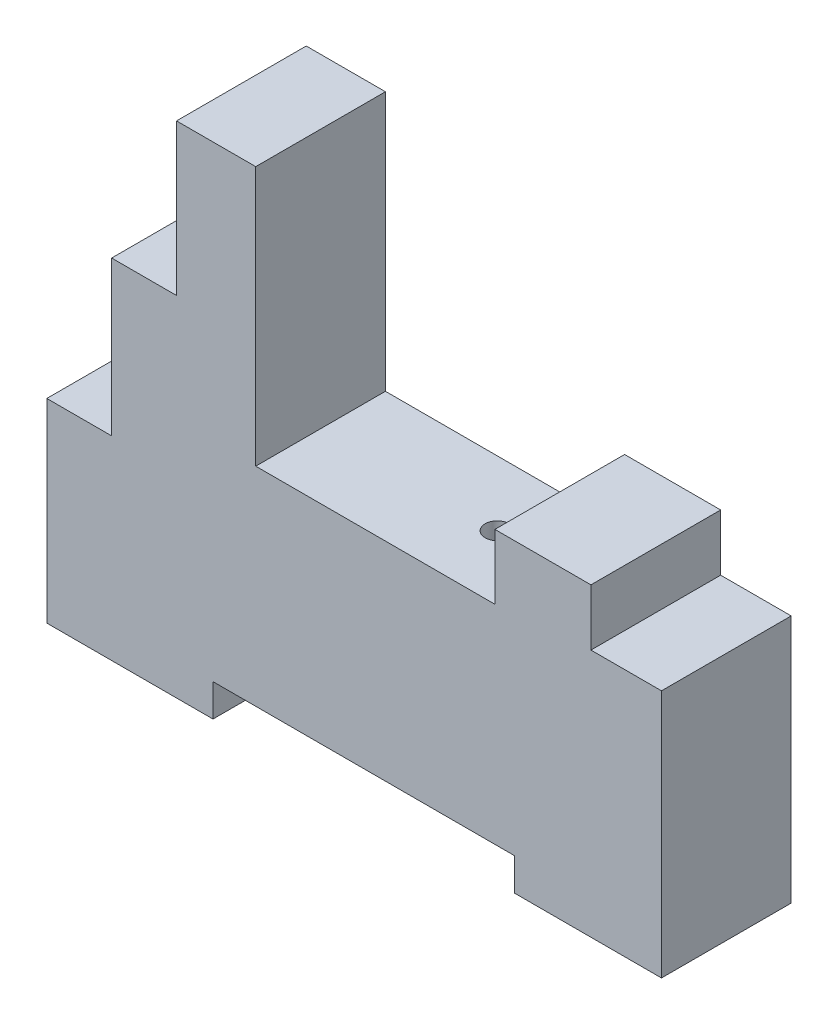
SolidWorks part; units mm, degrees
ref_plane "Front Plane" through (0, 0, 0) normal (0, 0, 1) x (1, 0, 0)
ref_plane "Top Plane" through (0, 0, 0) normal (0, 1, 0) x (1, 0, 0)
ref_plane "Right Plane" through (0, 0, 0) normal (1, 0, 0) x (0, 0, -1)
sketch "Sketch1" plane through (0, 0, 0) normal (0, 0, 1) x (1, 0, 0)
  line L0 (0, 0) -> (0, 24)
  line L1 (0, 24) -> (8, 24)
  line L2 (8, 24) -> (8, 43)
  line L3 (8, 43) -> (16, 43)
  line L4 (16, 43) -> (16, 61.65)
  line L5 (16, 61.65) -> (25.77, 61.65)
  line L6 (25.77, 61.65) -> (25.77, 29.65)
  line L7 (25.77, 29.65) -> (55.27, 29.65)
  line L8 (55.27, 29.65) -> (55.27, 37.65)
  line L9 (55.27, 37.65) -> (67.12, 37.65)
  line L10 (67.12, 37.65) -> (67.12, 30.68)
  line L11 (67.12, 30.68) -> (75.82, 30.68)
  line L12 (75.82, 30.68) -> (75.82, 0)
  line L13 (75.82, 0) -> (57.7, 0)
  line L14 (57.7, 0) -> (57.7, 4)
  line L15 (57.7, 4) -> (20.5, 4)
  line L16 (20.5, 4) -> (20.5, 0)
  line L17 (20.5, 0) -> (0, 0)
  dimension "D1" = 24
  dimension "D2" = 43
  dimension "D3" = 61.65
  dimension "D4" = 8
  dimension "D5" = 32
  dimension "D6" = 29.5
  dimension "D7" = 8
  dimension "D8" = 11.85
  dimension "D9" = 8.7
  dimension "D10" = 4
  dimension "D11" = 37.2
  dimension "D12" = 20.5
  dimension "D14" = 30.68
  dimension "D15" = 9.77
extrude "Boss-Extrude1" add sketch "Sketch1" along normal blind 16
sketch "Sketch2" plane through (0, 29.65, 0) normal (0, 1, 0) x (1, 0, 0)
  line L0 (75.82, -16) -> (75.82, 0) construction
  circle A0 centre (47.57, -8) radius 1.5
  point P2 (75.82, -8)
  dimension "D1" = 3
  dimension "D2" = 28.25
extrude "Cut-Extrude1" cut sketch "Sketch2" against normal through all
